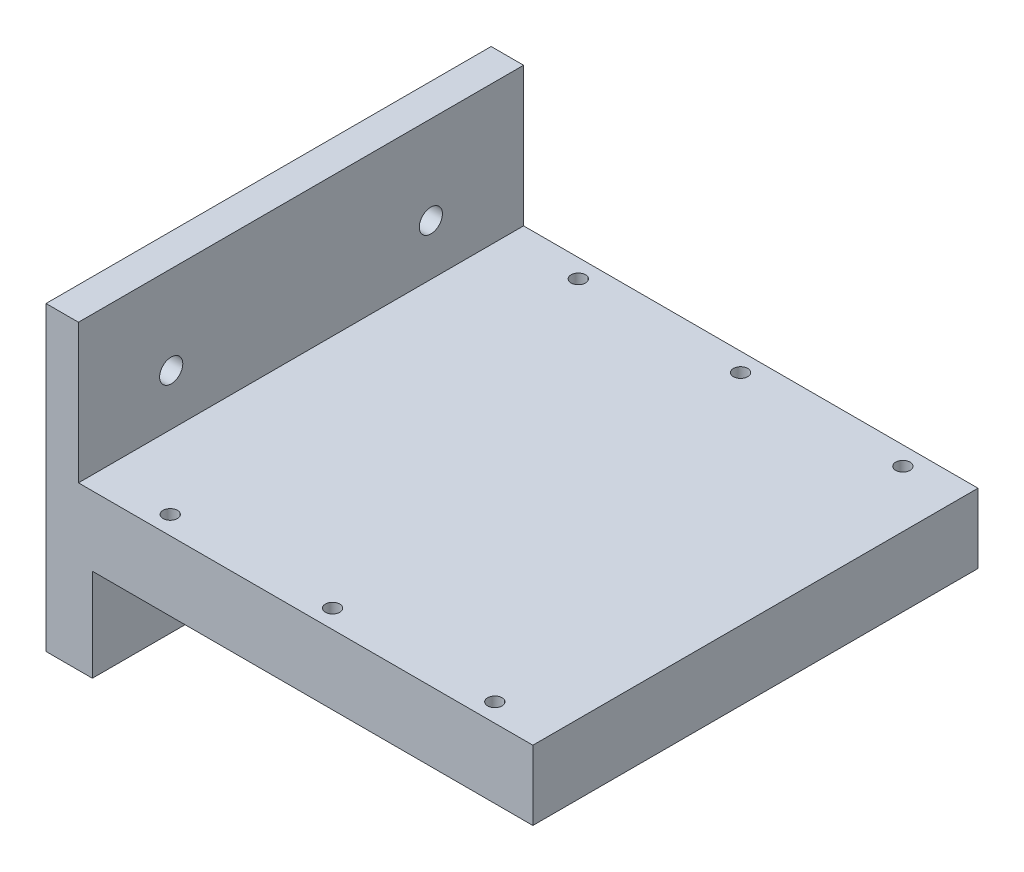
SolidWorks part; units mm, degrees
ref_plane "Ebene vorne" through (0, 0, 0) normal (0, 0, 1) x (1, 0, 0)
ref_plane "Ebene oben" through (0, 0, 0) normal (0, 1, 0) x (1, 0, 0)
ref_plane "Ebene rechts" through (0, 0, 0) normal (1, 0, 0) x (0, 0, -1)
sketch "Skizze1" plane through (0, 0, 0) normal (0, 0, 1) x (1, 0, 0)
  line L1 (-52.5, -7.5) -> (52.5, -7.5)
  line L2 (-52.5, -7.5) -> (-52.5, 7.5)
  line L3 (-52.5, 7.5) -> (52.5, 7.5)
  line L4 (52.5, -7.5) -> (52.5, 7.5)
  line L5 (-52.5, -7.5) -> (52.5, 7.5) construction
  line L6 (-52.5, 7.5) -> (52.5, -7.5) construction
  point P0 (0, 0)
  dimension "D1" = 105
  dimension "D2" = 15
extrude "Aufsatz-Linear austragen1" add sketch "Skizze1" along normal blind 96
sketch "Skizze2" plane through (0, 7.5, 0) normal (0, 1, 0) x (1, 0, 0)
  line L0 (52.5, 0) -> (-52.5, 0) construction
  line L1 (52.5, 0) -> (24.5, 0)
  line L2 (52.5, 0) -> (52.5, -96)
  line L3 (52.5, -96) -> (24.5, -96)
  line L4 (24.5, 0) -> (24.5, -96)
  line L5 (52.5, -96) -> (-52.5, -96) construction
  line L6 (52.5, -96) -> (52.5, 0) construction
  line L8 (17.5, 0) -> (-10.5, 0)
  line L9 (17.5, 0) -> (17.5, -96)
  line L10 (17.5, -96) -> (-10.5, -96)
  line L11 (-10.5, 0) -> (-10.5, -96)
  line L12 (-17.5, 0) -> (-45.5, 0)
  line L13 (-17.5, 0) -> (-17.5, -96)
  line L14 (-17.5, -96) -> (-45.5, -96)
  line L15 (-45.5, 0) -> (-45.5, -96)
  dimension "D1" = 28
  dimension "D2" = 0
  dimension "D3" = 28
  dimension "D4" = 28
  dimension "D5" = 7
  dimension "D6" = 7
sketch "Skizze3" plane through (0, 7.5, 0) normal (0, 1, 0) x (1, 0, 0)
  line L1 (-45.5, 0) -> (-52.5, 0)
  line L2 (-45.5, 0) -> (-45.5, -96)
  line L3 (-45.5, -96) -> (-52.5, -96)
  line L4 (-52.5, 0) -> (-52.5, -96)
extrude "Aufsatz-Linear austragen2" add sketch "Skizze3" along normal blind 30
sketch "Skizze4" plane through (0, -7.5, 0) normal (0, -1, 0) x (1, 0, 0)
  line L0 (-17.5, 0) -> (-45.5, 0) construction
  line L1 (-52.5, 96) -> (-42.5, 96)
  line L2 (-52.5, 96) -> (-52.5, 0)
  line L3 (-52.5, 0) -> (-42.5, 0)
  line L4 (-42.5, 96) -> (-42.5, 0)
  dimension "D1" = 10
extrude "Aufsatz-Linear austragen3" add sketch "Skizze4" along normal blind 20
sketch "Skizze5" plane through (0, 7.5, 0) normal (0, 1, 0) x (1, 0, 0)
  line L0 (52.5, 0) -> (52.5, -96) construction
  line L1 (17.5, 0) -> (17.5, -96) construction
  line L2 (-17.5, 0) -> (-17.5, -96) construction
  line L4 (52.5, -96) -> (24.5, -96) construction
  line L5 (17.5, -96) -> (-10.5, -96) construction
  line L6 (-17.5, -96) -> (-45.5, -96) construction
  circle A0 centre (40.3, -92) radius 1.55
  circle A1 centre (40.3, -4) radius 1.55
  circle A2 centre (5.3, -4) radius 1.55
  circle A3 centre (5.3, -92) radius 1.55
  circle A4 centre (-29.7, -4) radius 1.55
  circle A5 centre (-29.7, -92) radius 1.55
  dimension "D7" = 4
  dimension "D11" = 4
  dimension "D1" = 12.2
  dimension "D2" = 12.2
  dimension "D3" = 12.2
  dimension "D4" = 12.2
  dimension "D5" = 12.2
  dimension "D6" = 12.2
  dimension "D8" = 88
  dimension "D9" = 88
  dimension "D10" = 88
  dimension "D12" = 4
extrude "Schnitt-Linear austragen1" cut sketch "Skizze5" against normal blind 20
sketch "Skizze6" plane through (-42.5, 0, 0) normal (1, 0, 0) x (0, 0, -1)
  line L0 (0, -27.5) -> (0, -7.5) construction
  line L1 (-96, -27.5) -> (-96, -7.5) construction
  line L2 (0, -27.5) -> (-96, -27.5) construction
  circle A0 centre (-76, -19.5) radius 2.5
  circle A1 centre (-20, -19.5) radius 2.5
  dimension "D1" = 5
  dimension "D2" = 5
  dimension "D3" = 20
  dimension "D4" = 20
  dimension "D5" = 8
  dimension "D6" = 8
extrude "Schnitt-Linear austragen2" cut sketch "Skizze6" against normal blind 20
ref_plane "Ebene3" through (0, -0.5, 0) normal (0, 1, 0) x (1, 0, 0)
mirror "Spiegeln1" about plane through (0, -0.5, 0) normal (0, 1, 0) of "Schnitt-Linear austragen2"
